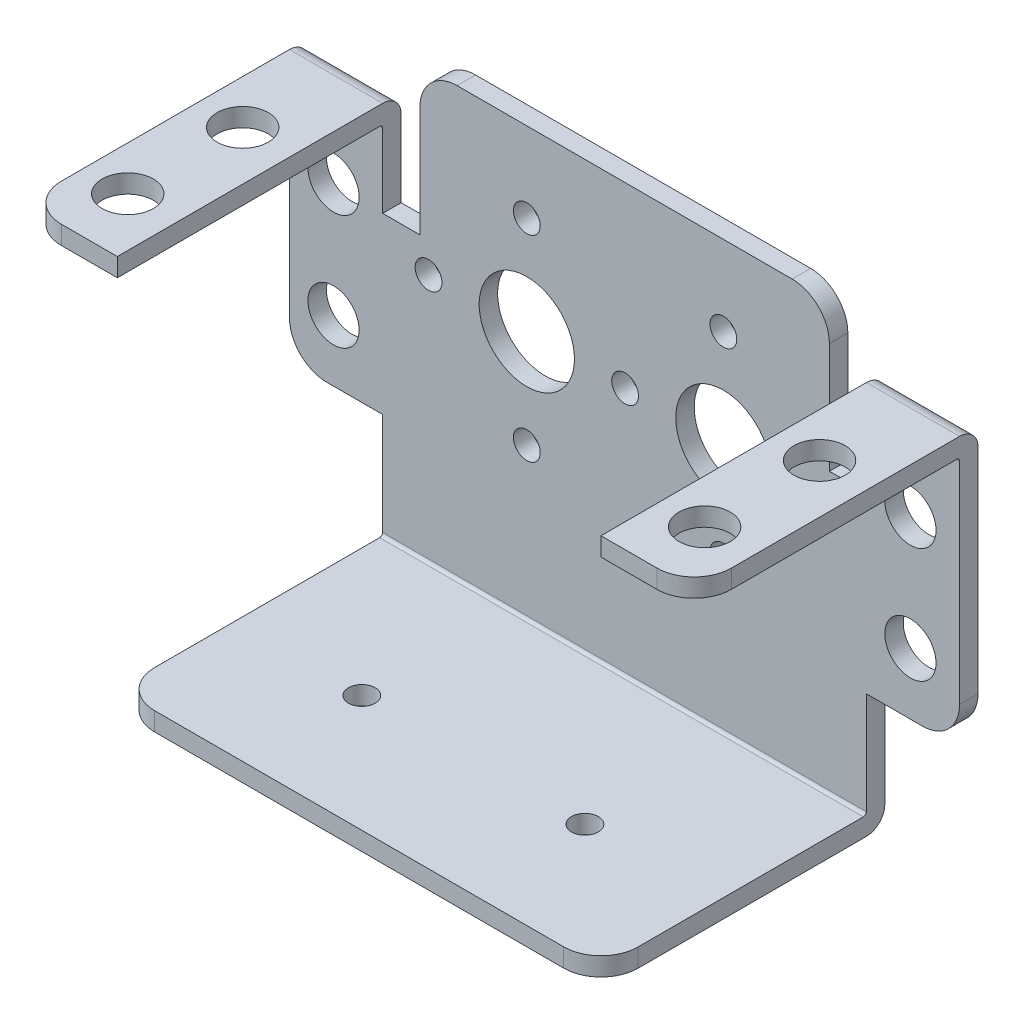
SolidWorks part; units mm, degrees
material "6061 Alloy"
ref_plane "Front Plane" through (0, 0, 0) normal (0, 0, 1) x (1, 0, 0)
ref_plane "Top Plane" through (0, 0, 0) normal (0, 1, 0) x (1, 0, 0)
ref_plane "Right Plane" through (0, 0, 0) normal (1, 0, 0) x (0, 0, -1)
sketch "Sketch1" plane through (0, 0, 0) normal (0, 0, 1) x (1, 0, 0)
  line L0 (11.9126, 30.734) -> (11.9126, 34.836)
  line L1 (8.7376, 0) -> (49.9872, 0)
  line L2 (0.7874, 13.716) -> (0.7874, 33.528)
  line L3 (0.7874, 33.528) -> (8.7376, 33.528)
  line L4 (57.9374, 13.716) -> (57.9374, 33.528)
  line L5 (15.0876, 38.011) -> (43.6626, 38.011)
  line L6 (46.8376, 34.836) -> (46.8376, 33.528)
  line L7 (49.9872, 33.528) -> (57.9374, 33.528)
  line L8 (3.9624, 10.541) -> (8.7376, 10.541)
  line L9 (8.7376, 10.541) -> (8.7376, 0)
  line L10 (49.9872, 0) -> (49.9872, 10.541)
  line L11 (49.9872, 10.541) -> (54.7624, 10.541)
  line L12 (11.9126, 30.734) -> (11.9126, 25.4)
  line L13 (11.9126, 25.4) -> (8.7376, 25.4)
  line L14 (8.7376, 25.4) -> (8.7376, 33.528)
  line L15 (46.8376, 33.528) -> (46.8376, 25.4)
  line L16 (46.8376, 25.4) -> (49.9872, 25.4)
  line L17 (49.9872, 25.4) -> (49.9872, 33.528)
  arc A0 (11.9126, 34.836) -> (15.0876, 38.011) centre (15.0876, 34.836) cw
  arc A1 (43.6626, 38.011) -> (46.8376, 34.836) centre (43.6626, 34.836) cw
  arc A2 (3.9624, 10.541) -> (0.7874, 13.716) centre (3.9624, 13.716) cw
  arc A3 (54.7624, 10.541) -> (57.9374, 13.716) centre (54.7624, 13.716) ccw
  circle A4 centre (21.0312, 22.8092) radius 4.064
  circle A6 centre (21.0312, 31.1912) radius 1.143
  circle A7 centre (29.4132, 22.8092) radius 1.143
  circle A8 centre (21.0312, 14.4272) radius 1.143
  circle A9 centre (12.6492, 22.8092) radius 1.143
  circle A10 centre (37.7952, 31.1912) radius 1.143
  circle A11 centre (46.1772, 22.8092) radius 1.143
  circle A12 centre (37.7952, 22.8092) radius 4.064
  circle A13 centre (37.7952, 14.4272) radius 1.143
  circle A14 centre (4.5466, 25.5778) radius 2.1844
  circle A15 centre (4.5466, 15.7734) radius 2.1844
  circle A16 centre (53.7464, 25.5778) radius 2.1844
  circle A17 centre (53.7464, 15.7734) radius 2.1844
  dimension "D5" = 3.175
  dimension "D1" = 3.175
  dimension "D10" = 8.128
  dimension "D11" = 21.0312
  dimension "D12" = 2.286
  dimension "D15" = 4.3688
  dimension "D16" = 4.3688
  dimension "D18" = 4.3688
  dimension "D20" = 4.3688
  dimension "D30" = 22.8092
  dimension "D34" = 8.128
  dimension "D35" = 2.286
  dimension "D36" = 2.286
  dimension "D37" = 2.286
  dimension "D2" = 22.8092
  dimension "D3" = 11.1252
  dimension "D4" = 46.0502
  dimension "D6" = 10.541
  dimension "D7" = 10.541
  dimension "D8" = 7.9502
  dimension "D9" = 49.1998
  dimension "D13" = 20.2438
  dimension "D14" = 25.5778
  dimension "D17" = 15.7734
  dimension "D19" = 25.5778
  dimension "D21" = 7.9502
  dimension "D22" = 25.4
  dimension "D23" = 25.4
  dimension "D24" = 49.1998
  dimension "D25" = 3.7592
  dimension "D26" = 3.7592
  dimension "D27" = 52.959
  dimension "D28" = 15.7734
  dimension "D29" = 52.959
  dimension "D31" = 8.382
  dimension "D32" = 8.382
  dimension "D38" = 8.382
  dimension "D39" = 8.382
  dimension "D40" = 8.382
  dimension "D41" = 33.528
  dimension "D42" = 34.836
  dimension "D33" = 4
extrude "Extrude2" add sketch "Sketch1" along normal blind 1.5748
sketch "Sketch3" plane through (0, 0, 1.5748) normal (0, 0, 1) x (1, 0, 0)
  line L0 (8.7376, 25.4) -> (8.7376, 33.528) construction
  line L1 (0.7874, 33.528) -> (8.7376, 33.528)
  line L2 (0.7874, 33.528) -> (0.7874, 31.9532)
  line L3 (0.7874, 31.9532) -> (8.7376, 31.9532)
  line L4 (8.7376, 33.528) -> (8.7376, 31.9532)
  line L5 (8.7376, 10.541) -> (8.7376, 0) construction
  line L6 (8.7376, 1.5748) -> (49.9872, 1.5748)
  line L7 (8.7376, 1.5748) -> (8.7376, 0)
  line L8 (8.7376, 0) -> (49.9872, 0)
  line L9 (49.9872, 1.5748) -> (49.9872, 0)
  line L10 (57.9374, 13.716) -> (57.9374, 33.528) construction
  line L11 (49.9872, 33.528) -> (57.9374, 33.528)
  line L12 (49.9872, 33.528) -> (49.9872, 31.9532)
  line L13 (49.9872, 31.9532) -> (57.9374, 31.9532)
  line L14 (57.9374, 33.528) -> (57.9374, 31.9532)
  dimension "D1" = 1.5748
  dimension "D2" = 1.5748
extrude "Extrude3" add sketch "Sketch3" along normal blind 22.6314
fillet "Fillet1" radius 3.175 4 edges at (8.7376, 0.7874, 24.2062) (49.9872, 0.7874, 24.2062) (57.9374, 32.7406, 24.2062) (0.7874, 32.7406, 24.2062)
fillet "Fillet2" radius 1.5748 3 edges at (29.3624, 0, 0) (4.7625, 33.528, 0) (53.9623, 33.528, 0)
fillet "Fillet3" radius 0.254 3 edges at (29.3624, 1.5748, 1.5748) (4.7625, 31.9532, 1.5748) (53.9623, 31.9532, 1.5748)
sketch "Sketch4" plane through (0, 0, 0) normal (0, -1, 0) x (1, 0, 0)
  line L0 (49.9872, 0) -> (8.7376, 0) construction
  line L1 (0.7874, 21.0312) -> (0.7874, 1.8288) construction
  line L2 (49.9872, 21.0312) -> (49.9872, 1.8288) construction
  circle A0 centre (19.6342, 14.2494) radius 1.143
  circle A6 centre (38.6588, 14.2494) radius 1.143
  dimension "D1" = 14.2494
  dimension "D2" = 2.286
  dimension "D3" = 18.8468
  dimension "D4" = 2.286
  dimension "D5" = 11.3284
extrude "Extrude4" cut sketch "Sketch4" against normal up to surface (1.5748 mm away) up to face at (29.3624, 1.5748, 15.9079)
sketch "Sketch5" plane through (0, 33.528, 0) normal (0, 1, 0) x (1, 0, 0)
  line L0 (0.7874, -21.0312) -> (0.7874, -1.5748) construction
  line L1 (43.6626, 0) -> (15.0876, 0) construction
  circle A0 centre (4.5466, -9.3218) radius 2.1844
  circle A1 centre (4.5466, -19.1262) radius 2.1844
  circle A2 centre (53.7464, -19.1262) radius 2.1844
  circle A3 centre (53.7464, -9.3218) radius 2.1844
  dimension "D1" = 4.3688
  dimension "D2" = 4.3688
  dimension "D3" = 3.7592
  dimension "D4" = 9.3218
  dimension "D5" = 19.1262
extrude "Extrude5" cut sketch "Sketch5" against normal up to surface (1.5748 mm away) up to face at (4.471, 31.9532, 14.7518)
